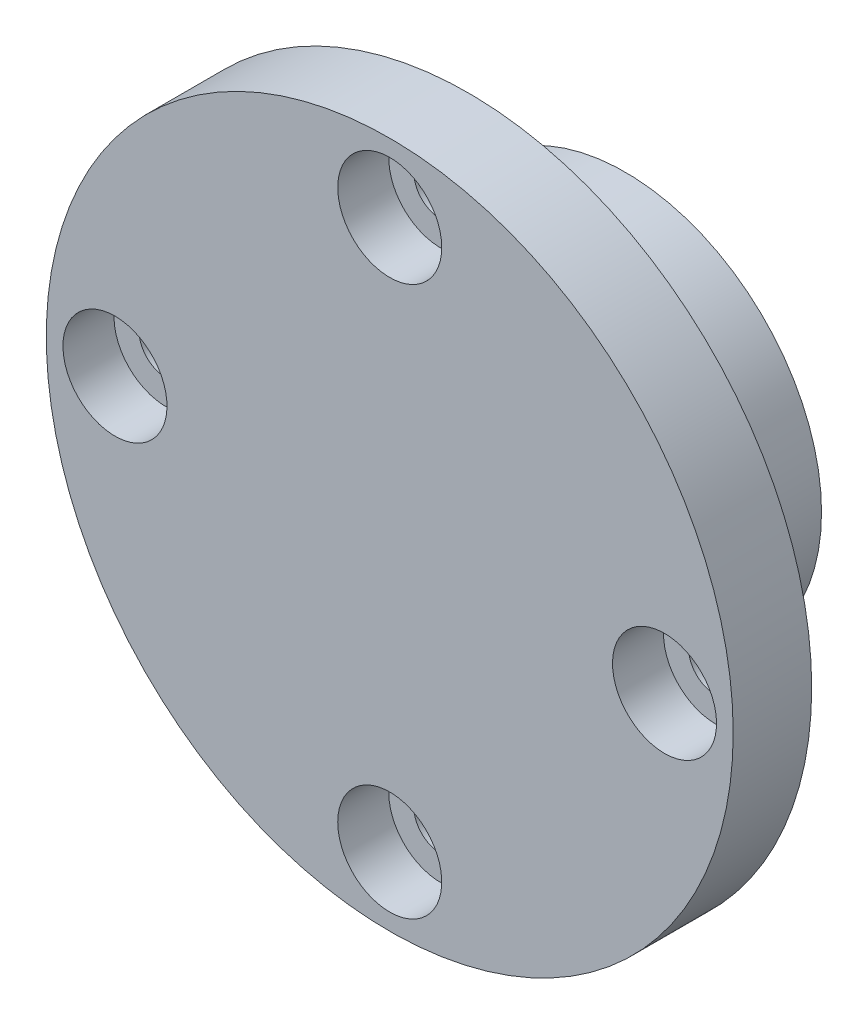
SolidWorks part; units mm, degrees
ref_plane "Front Plane" through (0, 0, 0) normal (0, 0, 1) x (1, 0, 0)
ref_plane "Top Plane" through (0, 0, 0) normal (0, 1, 0) x (1, 0, 0)
ref_plane "Right Plane" through (0, 0, 0) normal (1, 0, 0) x (0, 0, -1)
sketch "Sketch1" plane through (0, 0, 0) normal (0, 0, 1) x (1, 0, 0)
  line L1 (7.3323, 0) -> (3.6662, 6.35)
  line L2 (3.6662, 6.35) -> (-3.6662, 6.35)
  line L3 (-3.6662, 6.35) -> (-7.3323, 0)
  line L4 (-7.3323, 0) -> (-3.6662, -6.35)
  line L5 (-3.6662, -6.35) -> (3.6662, -6.35)
  line L6 (3.6662, -6.35) -> (7.3323, 0)
  circle A0 centre (0, 0) radius 10
  circle A1 centre (0, 0) radius 6.35 construction
  dimension "D2" = 20
  dimension "D1" = 12.7
extrude "Boss-Extrude1" add sketch "Sketch1" along normal blind 8
sketch "Sketch2" plane through (0, 0, 8) normal (0, 0, 1) x (1, 0, 0)
  circle A0 centre (0, 0) radius 17.5
  dimension "D1" = 35
extrude "Boss-Extrude2" add sketch "Sketch2" along normal blind 4
sketch "Sketch3" plane through (0, 0, 8) normal (0, 0, -1) x (-1, 0, 0)
  circle A0 centre (0, 14) radius 1.375
  dimension "D1" = 2.75
  dimension "D2" = 14
extrude "Cut-Extrude1" cut sketch "Sketch3" against normal up to next
pattern_circular "CirPattern1" count 4 over 360 about axis through (0, 0, 0) along (0, 0, 1) of "Cut-Extrude1"
sketch "Sketch4" plane through (0, 0, 12) normal (0, 0, 1) x (1, 0, 0)
  circle A0 centre (0, 14) radius 2.65
  dimension "D1" = 5.3
extrude "Cut-Extrude2" cut sketch "Sketch4" against normal blind 2.6
pattern_circular "CirPattern2" count 4 over 360 about axis through (0, 0, 0) along (0, 0, 1) of "Cut-Extrude2"
